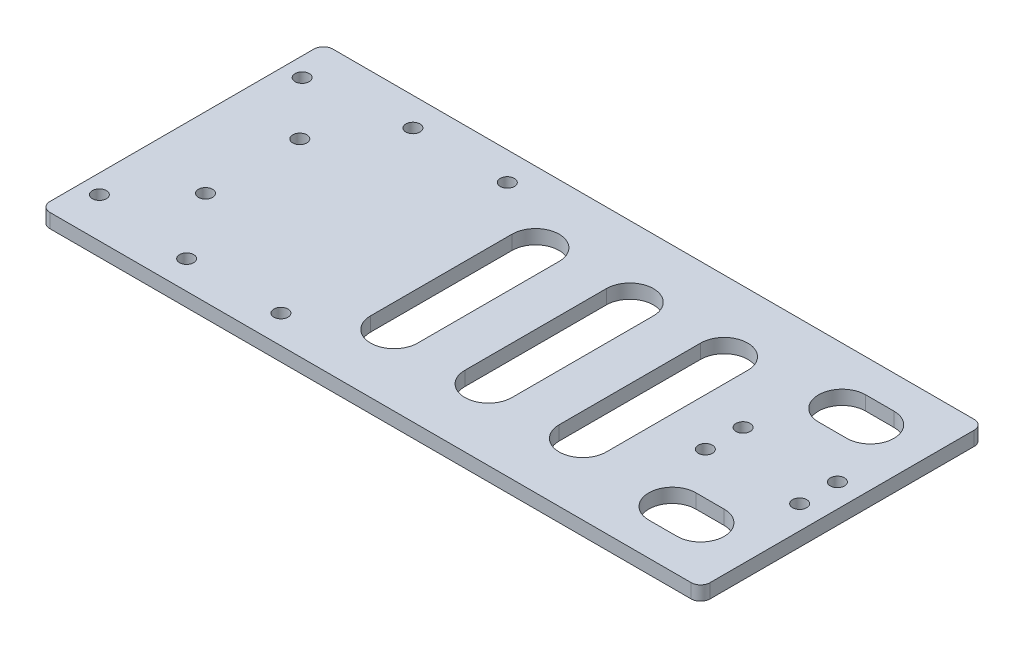
SolidWorks part; units mm, degrees
ref_plane "前视基准面" through (0, 0, 0) normal (0, 0, 1) x (1, 0, 0)
ref_plane "上视基准面" through (0, 0, 0) normal (0, 1, 0) x (1, 0, 0)
ref_plane "右视基准面" through (0, 0, 0) normal (1, 0, 0) x (0, 0, -1)
other "Configuration Table"
sketch "草图1" plane through (0, 0, 0) normal (0, 1, 0) x (1, 0, 0)
  line L0 (-60, 10) -> (-60, -10) construction
  line L1 (-65, 30) -> (65, 30)
  line L2 (-65, 30) -> (-65, -30) construction
  line L3 (-65, -30) -> (65, -30)
  line L4 (65, 30) -> (65, -30)
  line L5 (-65, 30) -> (65, -30) construction
  line L6 (-65, -30) -> (65, 30) construction
  line L7 (-60, 0) -> (0, 0) construction
  line L8 (-50, -24) -> (-30, -24) construction
  line L9 (-65, 30) -> (-75, 30)
  line L10 (-75, 30) -> (-75, -30)
  line L11 (-75, -30) -> (-65, -30)
  line L12 (-71, 21.5) -> (-71, -21.5) construction
  line L13 (-71, 0) -> (-75, 0) construction
  circle A0 centre (-60, 10) radius 1.5
  circle A1 centre (-60, -10) radius 1.5
  circle A2 centre (-50, -24) radius 1.5
  circle A3 centre (-30, -24) radius 1.5
  circle A4 centre (-30, 24) radius 1.5
  circle A5 centre (-50, 24) radius 1.5
  circle A6 centre (-71, 21.5) radius 1.5
  circle A7 centre (-71, -21.5) radius 1.5
  point P0 (0, 0)
  dimension "D3" = 3
  dimension "D7" = 3
  dimension "D13" = 3
  dimension "D1" = 60
  dimension "D2" = 140
  dimension "D4" = 20
  dimension "D5" = 5
  dimension "D6" = 20
  dimension "D8" = 15
  dimension "D9" = 6
  dimension "D10" = 10
  dimension "D11" = 4
  dimension "D12" = 43
extrude "凸台-拉伸1" add sketch "草图1" along normal blind 3
sketch "草图3" plane through (0, 0, 0) normal (0, -1, 0) x (1, 0, 0)
  line L0 (40, 4) -> (60, 4) construction
  line L1 (65, 30) -> (65, -30) construction
  line L2 (-75, 30) -> (65, 30) construction
  line L3 (0, 0) -> (65, 0) construction
  circle A0 centre (40, 4) radius 1.5
  circle A1 centre (60, 4) radius 1.5
  circle A2 centre (60, -4) radius 1.5
  circle A3 centre (40, -4) radius 1.5
  dimension "D1" = 3
  dimension "D2" = 20
  dimension "D3" = 5
  dimension "D4" = 26
extrude "切除-拉伸1" cut sketch "草图3" against normal through all
sketch "草图4" plane through (0, 3, 0) normal (0, 1, 0) x (1, 0, 0)
  line L0 (-15, 15) -> (-15, -15) construction
  line L1 (-10, 15) -> (-10, -15)
  line L2 (-20, 15) -> (-20, -15)
  line L3 (-15, 0) -> (0, 0) construction
  line L6 (65, 30) -> (-75, 30) construction
  line L7 (5, 15) -> (5, -15) construction
  line L8 (10, 15) -> (10, -15)
  line L9 (0, 15) -> (0, -15)
  line L10 (25, 15) -> (25, -15) construction
  line L11 (30, 15) -> (30, -15)
  line L12 (20, 15) -> (20, -15)
  line L13 (40, 4) -> (60, 4) construction
  line L16 (47, -18) -> (53, -18) construction
  line L17 (50, 4) -> (50, 18) construction
  line L18 (47, 18) -> (53, 18) construction
  line L19 (47, 23) -> (53, 23)
  line L20 (47, 13) -> (53, 13)
  line L21 (47, -23) -> (53, -23)
  line L22 (47, -13) -> (53, -13)
  arc A0 (-10, 15) -> (-20, 15) centre (-15, 15) ccw
  arc A1 (-20, -15) -> (-10, -15) centre (-15, -15) ccw
  arc A4 (47, -23) -> (47, -13) centre (47, -18) cw
  arc A5 (10, 15) -> (0, 15) centre (5, 15) ccw
  arc A6 (0, -15) -> (10, -15) centre (5, -15) ccw
  arc A7 (30, 15) -> (20, 15) centre (25, 15) ccw
  arc A8 (20, -15) -> (30, -15) centre (25, -15) ccw
  arc A11 (47, 23) -> (47, 13) centre (47, 18) ccw
  arc A12 (53, 13) -> (53, 23) centre (53, 18) ccw
  arc A13 (53, -13) -> (53, -23) centre (53, -18) cw
  point P2 (-15, 0)
  point P16 (5, 0)
  point P23 (25, 0)
  point P32 (50, 18)
  point P43 (50, -18)
  dimension "D1" = 15
  dimension "D3" = 15
  dimension "D7" = 5
  dimension "D2" = 10
  dimension "D5" = 20
  dimension "D6" = 6
  dimension "D8" = 7
  dimension "D4" = 3
extrude "切除-拉伸2" cut sketch "草图4" against normal through all
fillet "圆角1" radius 2 4 edges at (65, 1.5, 30) (-75, 1.5, -30) (65, 1.5, -30) (-75, 1.5, 30)
